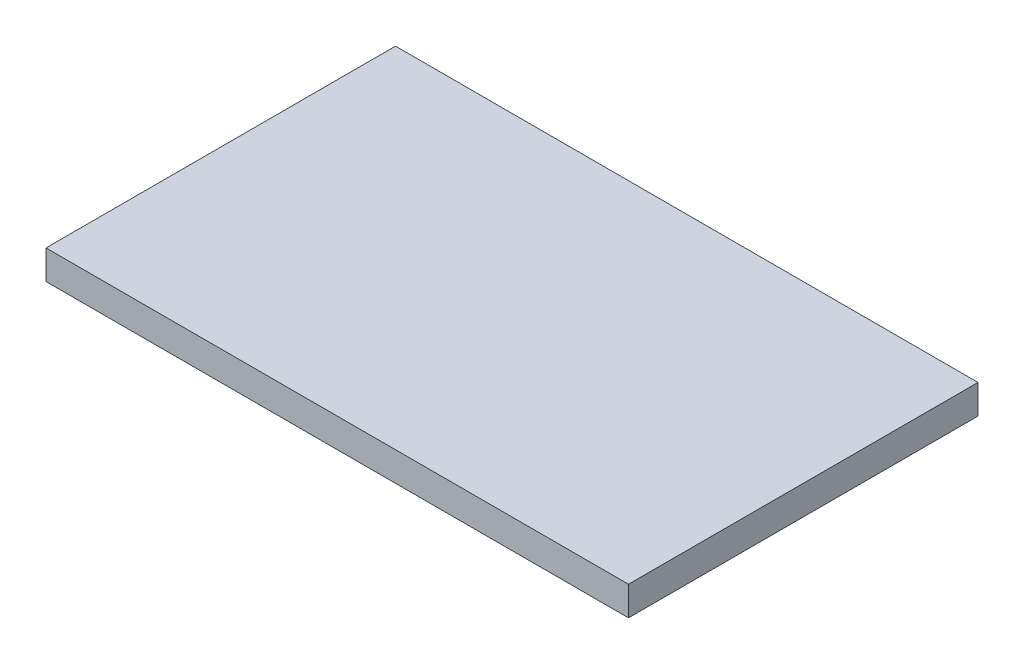
SolidWorks part; units mm, degrees
ref_plane "Front Plane" through (0, 0, 0) normal (0, 0, 1) x (1, 0, 0)
ref_plane "Top Plane" through (0, 0, 0) normal (0, 1, 0) x (1, 0, 0)
ref_plane "Right Plane" through (0, 0, 0) normal (1, 0, 0) x (0, 0, -1)
sketch "Sketch1" plane through (0, 0, 0) normal (0, 1, 0) x (1, 0, 0)
  line L1 (-254, -152.4) -> (254, -152.4)
  line L2 (-254, -152.4) -> (-254, 152.4)
  line L3 (-254, 152.4) -> (254, 152.4)
  line L4 (254, -152.4) -> (254, 152.4)
  line L5 (-254, -152.4) -> (254, 152.4) construction
  line L6 (-254, 152.4) -> (254, -152.4) construction
  point P0 (0, 0)
  dimension "D1" = 304.8
  dimension "D2" = 508
extrude "Boss-Extrude1" add sketch "Sketch1" along normal blind 25.4
